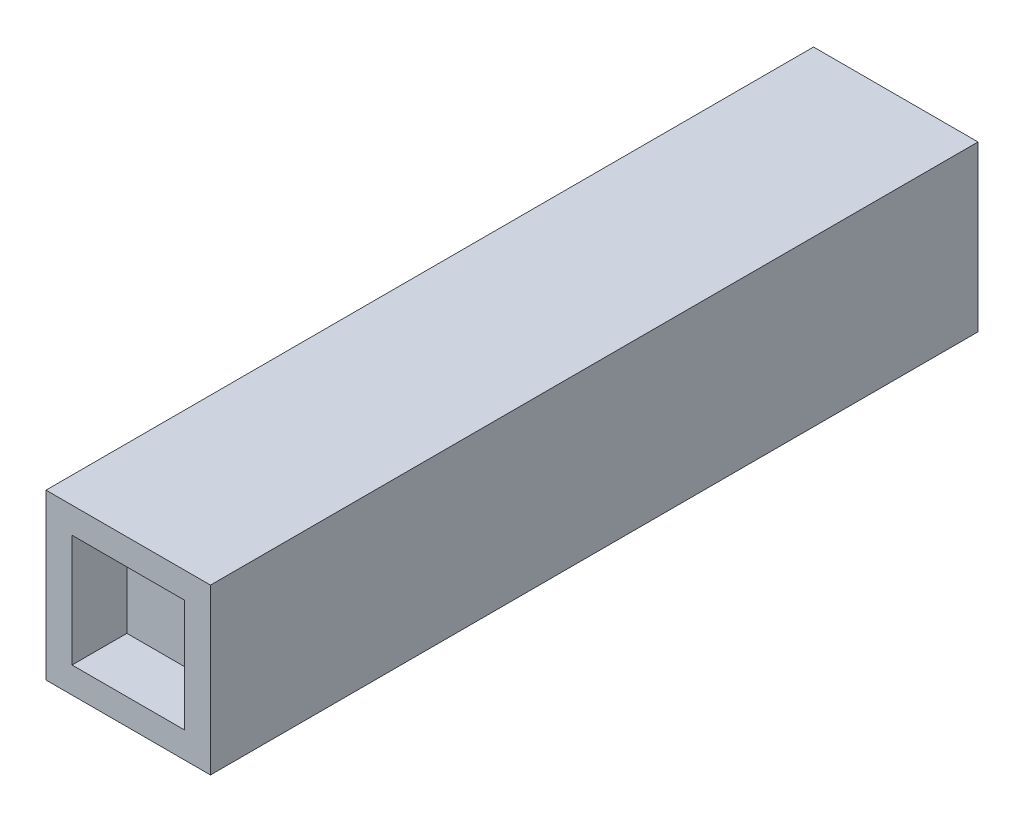
SolidWorks part; units mm, degrees
ref_plane "Front Plane" through (0, 0, 0) normal (0, 0, 1) x (1, 0, 0)
ref_plane "Top Plane" through (0, 0, 0) normal (0, 1, 0) x (1, 0, 0)
ref_plane "Right Plane" through (0, 0, 0) normal (1, 0, 0) x (0, 0, -1)
sketch "Sketch1" plane through (0, 0, 0) normal (0, 0, 1) x (1, 0, 0)
  line L1 (-15, -15) -> (15, -15)
  line L2 (-15, -15) -> (-15, 15)
  line L3 (-15, 15) -> (15, 15)
  line L4 (15, -15) -> (15, 15)
extrude "Boss-Extrude1" add sketch "Sketch1" along normal blind 140
sketch "Sketch2" plane through (0, 0, 0) normal (0, 0, 1) x (1, 0, 0)
  line L1 (-10, -10) -> (10, -10)
  line L2 (-10, -10) -> (-10, 10)
  line L3 (-10, 10) -> (10, 10)
  line L4 (10, -10) -> (10, 10)
extrude "Boss-Extrude2" add sketch "Sketch2" against normal blind 5
sketch "Sketch3" plane through (0, 0, 140) normal (0, 0, 1) x (1, 0, 0)
  line L1 (-10.25, -10.25) -> (10.25, -10.25)
  line L2 (-10.25, -10.25) -> (-10.25, 10.25)
  line L3 (-10.25, 10.25) -> (10.25, 10.25)
  line L4 (10.25, -10.25) -> (10.25, 10.25)
extrude "Cut-Extrude1" cut sketch "Sketch3" against normal blind 10
